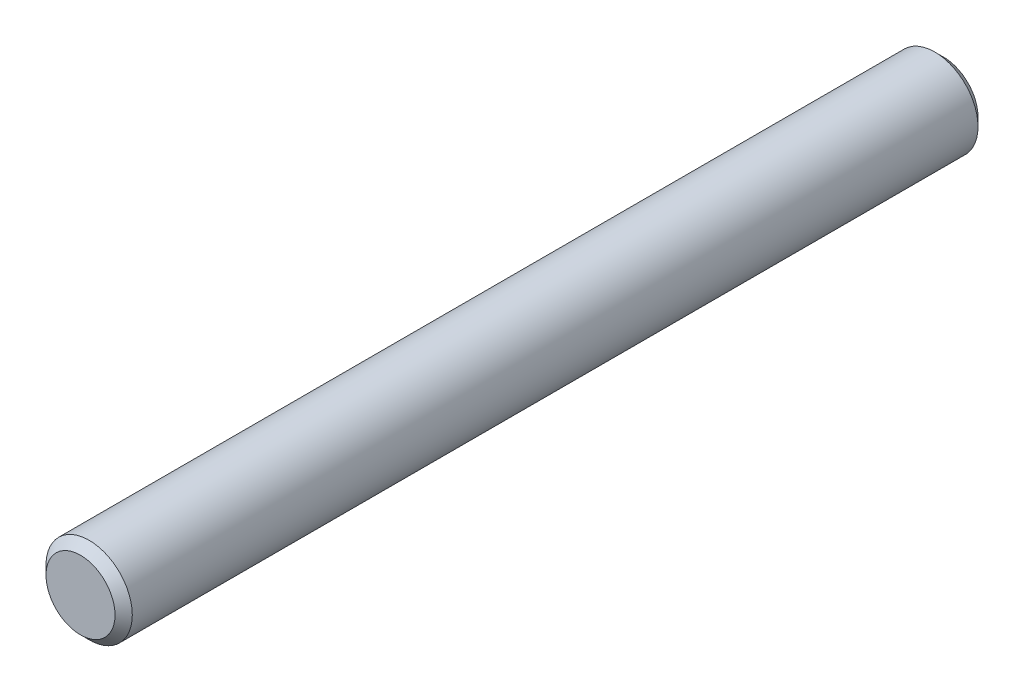
SolidWorks part; units mm, degrees
ref_plane "Front" through (0, 0, 0) normal (0, 0, 1) x (1, 0, 0)
ref_plane "Top" through (0, 0, 0) normal (0, 1, 0) x (1, 0, 0)
ref_plane "Right" through (0, 0, 0) normal (1, 0, 0) x (0, 0, -1)
sketch "Skizze1" plane through (0, 0, 0) normal (0, 0, 1) x (1, 0, 0)
  circle A0 centre (0, 0) radius 2.5
  dimension "D1" = 5
extrude "Aufsatz-Linear austragen1" add sketch "Skizze1" along normal blind 50
chamfer "Fase1" distance 0.5 angle 45 2 edges at (2.5, 0, 0) (2.5, 0, 50)
